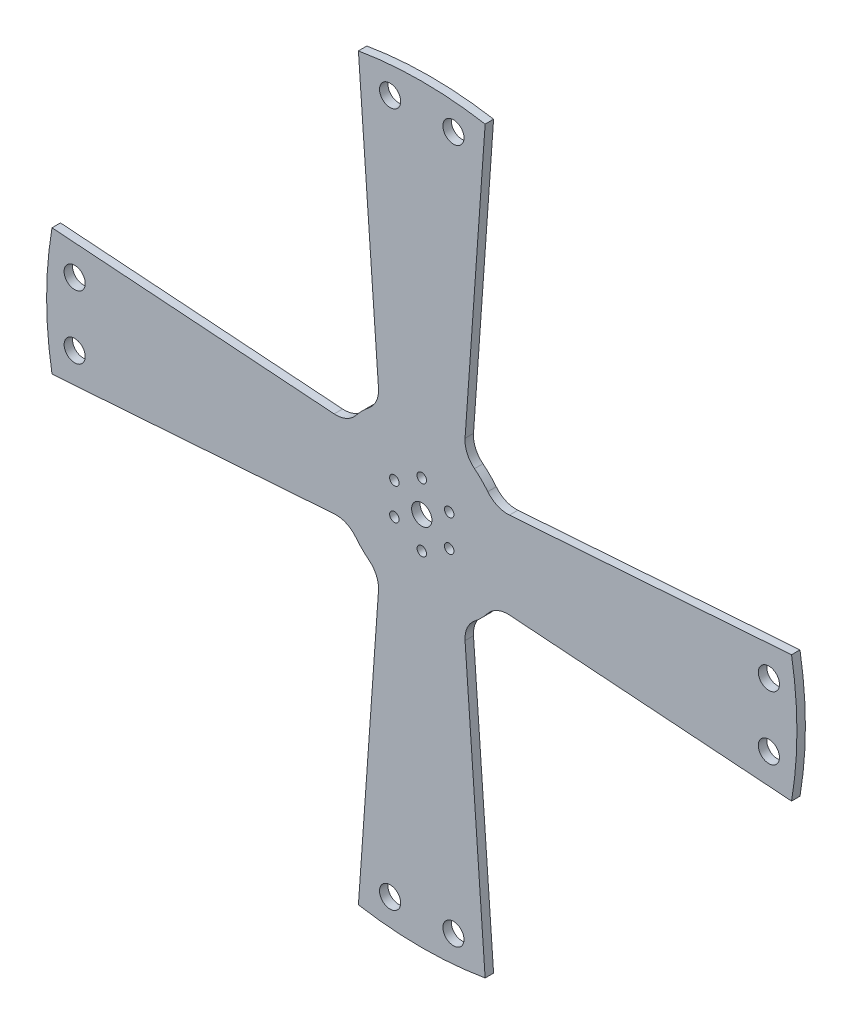
SolidWorks part; units mm, degrees
ref_plane "Front Plane" through (0, 0, 0) normal (0, 0, 1) x (1, 0, 0)
ref_plane "Top Plane" through (0, 0, 0) normal (0, 1, 0) x (1, 0, 0)
ref_plane "Right Plane" through (0, 0, 0) normal (1, 0, 0) x (0, 0, -1)
sketch "Sketch1" plane through (0, 0, 0) normal (0, 0, 1) x (1, 0, 0)
  line L0 (0, 0) -> (0, 112.7125) construction
  line L3 (-19.05, 111.1554) -> (-12.7, 21.997)
  line L4 (19.05, 111.1554) -> (12.7, 21.997)
  line L9 (111.1554, -19.05) -> (21.997, -12.7)
  line L10 (111.1554, 19.05) -> (21.997, 12.7)
  line L11 (-19.05, -111.1554) -> (-12.7, -21.997)
  line L12 (19.05, -111.1554) -> (12.7, -21.997)
  line L13 (-111.1554, 19.05) -> (-21.997, 12.7)
  line L14 (-111.1554, -19.05) -> (-21.997, -12.7)
  circle A2 centre (0, 0) radius 3.048
  arc A3 (19.05, 111.1554) -> (-19.05, 111.1554) centre (0, 0) ccw
  circle A7 centre (0, 0) radius 104.775 construction
  circle A8 centre (9.525, 104.3411) radius 3.175
  circle A9 centre (-9.525, 104.3411) radius 3.175
  arc A14 (-12.7, 21.997) -> (-21.997, 12.7) centre (0, 0) ccw
  arc A15 (111.1554, -19.05) -> (111.1554, 19.05) centre (0, 0) ccw
  circle A16 centre (104.3411, 9.525) radius 3.175
  circle A17 centre (104.3411, -9.525) radius 3.175
  arc A18 (-19.05, -111.1554) -> (19.05, -111.1554) centre (0, 0) ccw
  circle A19 centre (9.525, -104.3411) radius 3.175
  circle A20 centre (-9.525, -104.3411) radius 3.175
  arc A21 (-111.1554, 19.05) -> (-111.1554, -19.05) centre (0, 0) ccw
  circle A22 centre (-104.3411, -9.525) radius 3.175
  circle A23 centre (-104.3411, 9.525) radius 3.175
  arc A24 (21.997, 12.7) -> (12.7, 21.997) centre (0, 0) ccw
  arc A25 (12.7, -21.997) -> (21.997, -12.7) centre (0, 0) ccw
  arc A26 (-21.997, -12.7) -> (-12.7, -21.997) centre (0, 0) ccw
  point P43 (0, 0)
  dimension "D3" = 6.096
  dimension "D4" = 50.8
  dimension "D8" = 209.55
  dimension "D11" = 6.35
  dimension "D2" = 112.776
  dimension "D5" = 38.1
  dimension "D6" = 25.4
  dimension "D9" = 19.05
  dimension "D7" = 4
extrude "Boss-Extrude1" add sketch "Sketch1" along normal blind 2.54
fillet "Fillet1" radius 7.62 8 edges at (-21.997, -12.7, 1.27) (-12.7, -21.997, 1.27) (12.7, -21.997, 1.27) (21.997, -12.7, 1.27) (21.997, 12.7, 1.27) (12.7, 21.997, 1.27) (-21.997, 12.7, 1.27) (-12.7, 21.997, 1.27)
sketch "Sketch2" plane through (0, 0, 0) normal (0, 0, 1) x (1, 0, 0)
  line L0 (0, 0) -> (0, 35.3711) construction
  circle A0 centre (0, 0) radius 9.525 construction
  circle A1 centre (0, 9.525) radius 1.4224
  circle A2 centre (8.2489, 4.7625) radius 1.4224
  circle A3 centre (8.2489, -4.7625) radius 1.4224
  circle A4 centre (0, -9.525) radius 1.4224
  circle A5 centre (-8.2489, -4.7625) radius 1.4224
  circle A6 centre (-8.2489, 4.7625) radius 1.4224
  dimension "D1" = 19.05
  dimension "D2" = 2.8448
  dimension "D3" = 6
extrude "Cut-Extrude1" cut sketch "Sketch2" along normal through all
